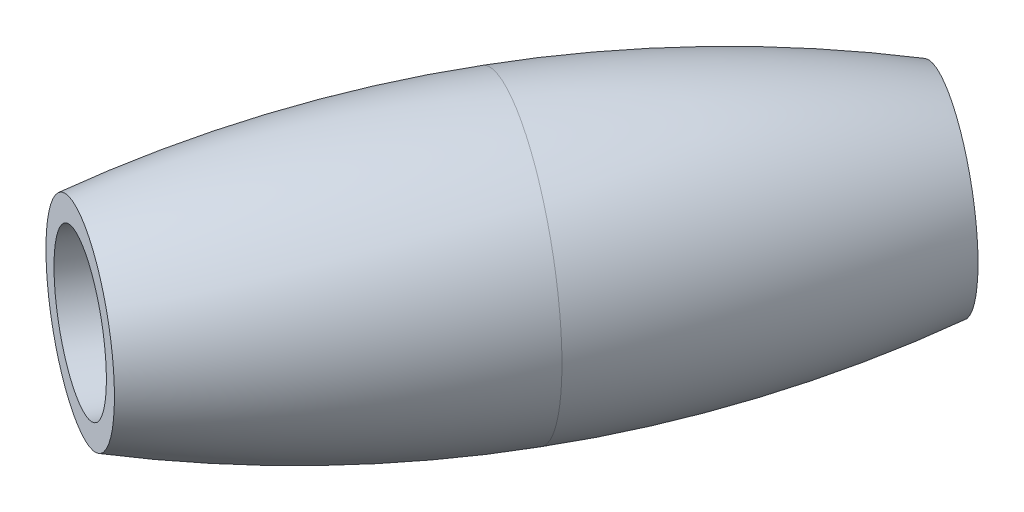
SolidWorks part; units mm, degrees
material "SANTOPRENE"
ref_plane "Front Plane" through (0, 0, 0) normal (0, 0, 1) x (1, 0, 0)
ref_plane "Top Plane" through (0, 0, 0) normal (0, 1, 0) x (1, 0, 0)
ref_plane "Right Plane" through (0, 0, 0) normal (1, 0, 0) x (0, 0, -1)
sketch "Sketch5" plane through (0, 0, 8.9658) normal (0, 1, 0) x (-1, 0, 0)
  line L0 (-35.3946, -1.2155) -> (-34.2645, -1.868)
  line L1 (-34.2645, -1.868) -> (-15.5145, 30.6079)
  line L2 (-15.5145, 30.6079) -> (-16.6446, 31.2604)
  line L3 (-25.9007, 4.1285) -> (-16.5257, 20.3664) construction
  arc A0 (-16.6446, 31.2604) -> (-28.228, 16.2974) centre (32.6591, -18.8723) ccw
  arc A1 (-28.228, 16.2974) -> (-35.3946, -1.2155) centre (32.6735, -18.8474) ccw
revolve "Revolve2" add sketch "Sketch5" angle 360 about L3
ref_plane "Plane1" through (-3.8823, 0, 6.7243) normal (0.5, 0, -0.866) x (-0.866, 0, -0.5)
sketch "Sketch6" plane through (-3.8823, 0, 6.7243) normal (0.5, 0, -0.866) x (-0.866, 0, -0.5)
  circle A0 centre (-28.9778, 0) radius 8.1
